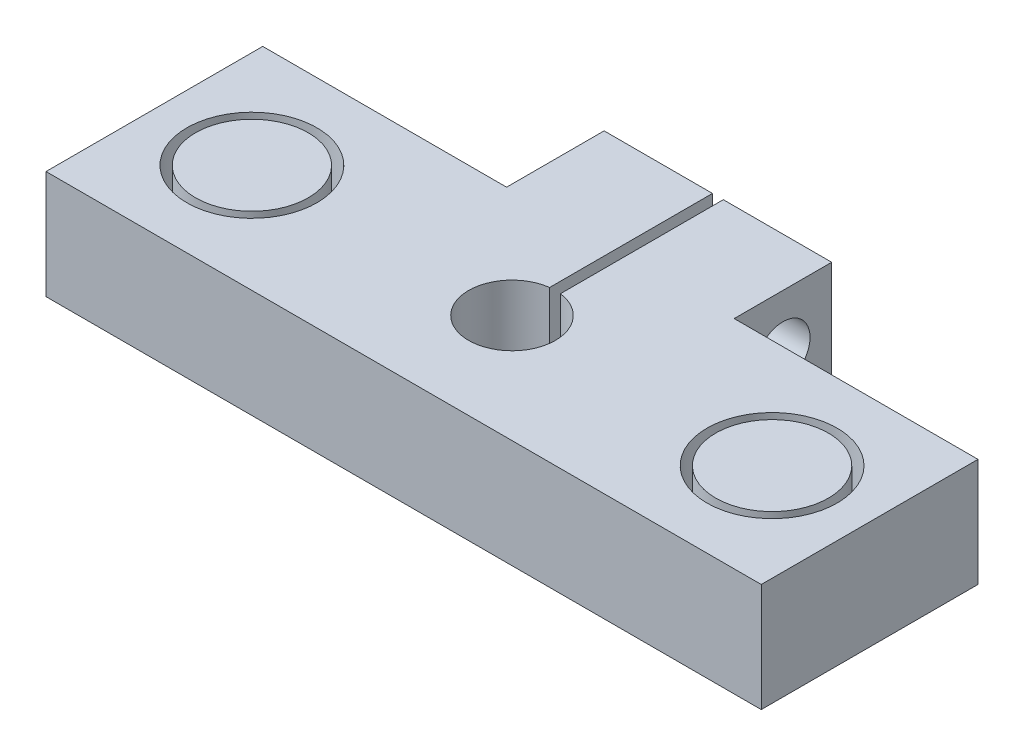
SolidWorks part; units mm, degrees
ref_plane "Front Plane" through (0, 0, 0) normal (0, 0, 1) x (1, 0, 0)
ref_plane "Top Plane" through (0, 0, 0) normal (0, 1, 0) x (1, 0, 0)
ref_plane "Right Plane" through (0, 0, 0) normal (1, 0, 0) x (0, 0, -1)
sketch "Sketch1" plane through (0, 0, 0) normal (0, 1, 0) x (1, 0, 0)
  line L0 (5.5, 19) -> (10.5, 19)
  line L1 (10.5, 19) -> (10.5, 10)
  line L2 (-5.5, 19) -> (-10.5, 19)
  line L3 (10.5, 10) -> (33, 10)
  line L4 (-24, -10) -> (24, -10)
  line L5 (-24, -10) -> (-33, -10)
  line L6 (24, -10) -> (33, -10)
  line L7 (33, -10) -> (33, 10)
  line L8 (-33, -10) -> (-33, 10)
  line L9 (0.5, 4) -> (0.5, 14)
  line L10 (-0.5, 4) -> (-0.5, 14)
  line L11 (-0.5, 14) -> (-0.5, 19)
  line L12 (-0.5, 19) -> (-5.5, 19)
  line L13 (-10.5, 19) -> (-10.5, 10)
  line L14 (-33, 10) -> (-10.5, 10)
  line L15 (-0.5, 4) -> (-0.5, 3.9686)
  line L16 (0.5, 4) -> (0.5, 3.9686)
  line L17 (0.5, 14) -> (0.5, 19)
  line L18 (0.5, 19) -> (5.5, 19)
  circle A0 centre (0, 0) radius 4
extrude "Boss-Extrude1" add sketch "Sketch1" along normal blind 10 contours A0 L15 L10 L11 L12 L2 L13 L14 L8 L5 L4 L6 L7 L3 L1 L0 L18 L17 L9 L16
sketch "Sketch2" plane through (10.5, 0, 0) normal (1, 0, 0) x (0, 0, -1)
  circle A0 centre (14.5, 5) radius 2.5
extrude "Cut-Extrude1" cut sketch "Sketch2" against normal blind 21
sketch "Sketch3" plane through (0, 10, 0) normal (0, 1, 0) x (1, 0, 0)
  circle A0 centre (24, 0) radius 6
  circle A1 centre (-24, 0) radius 6
extrude "Cut-Extrude2" cut sketch "Sketch3" against normal blind 5
sketch "Sketch4" plane through (0, 5, 0) normal (0, 1, 0) x (1, 0, 0)
  circle A0 centre (24, 0) radius 5.2
  circle A1 centre (-24, 0) radius 5.2
  dimension "D1" = 10.4
  dimension "D2" = 10.4
extrude "Boss-Extrude2" add sketch "Sketch4" along normal blind 5
